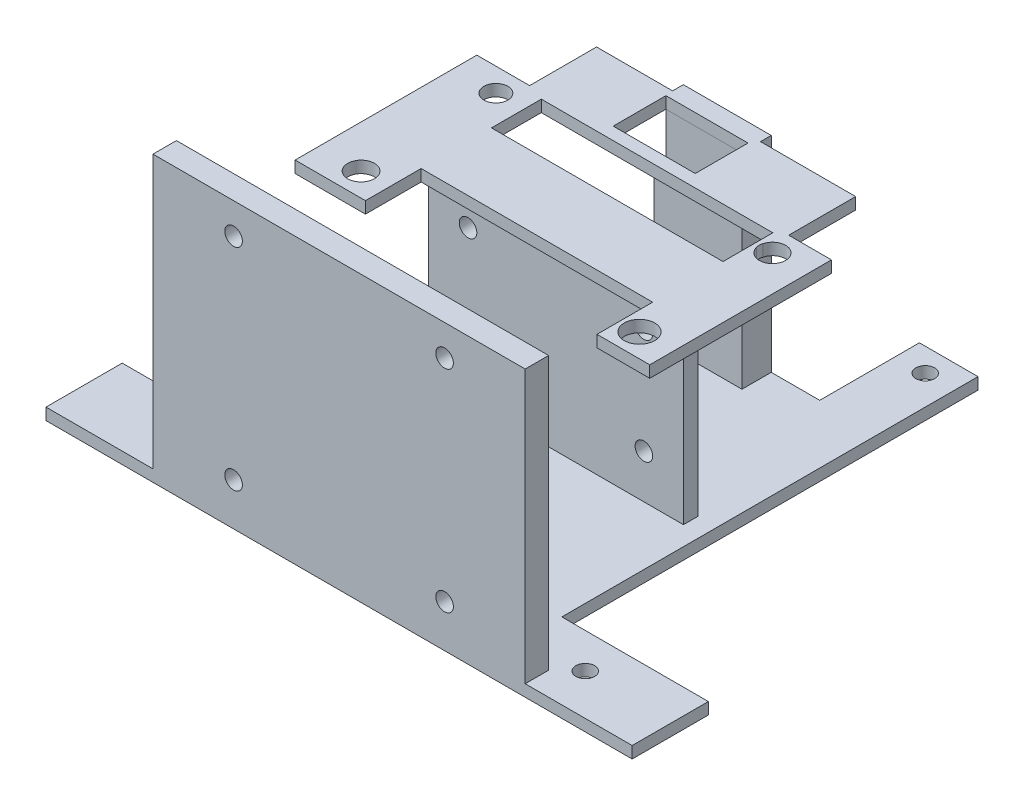
SolidWorks part; units mm, degrees
ref_plane "Alzado" through (0, 0, 0) normal (0, 0, 1) x (1, 0, 0)
ref_plane "Planta" through (0, 0, 0) normal (0, 1, 0) x (1, 0, 0)
ref_plane "Vista lateral" through (0, 0, 0) normal (1, 0, 0) x (0, 0, -1)
sketch "Croquis1" plane through (0, 0, 0) normal (0, 1, 0) x (1, 0, 0)
  line L0 (0, 42) -> (0, -42) construction
  line L1 (-25, 42) -> (25, 42)
  line L2 (-25, 42) -> (-25, -42)
  line L3 (-25, -42) -> (25, -42)
  line L4 (25, 42) -> (25, -42)
  line L5 (-25, -29) -> (-50, -29)
  line L7 (-25, -42) -> (-50, -42)
  line L8 (-50, -29) -> (-50, -42)
  line L13 (-25, 0) -> (25, 0) construction
  line L14 (25, -42) -> (50, -42)
  line L15 (25, -29) -> (50, -29)
  line L16 (50, -29) -> (50, -42)
  dimension "D1" = 84
  dimension "D2" = 50
  dimension "D3" = 13
  dimension "D4" = 25
extrude "Saliente-Extruir1" add sketch "Croquis1" along normal blind 2
sketch "Croquis2" plane through (0, 0, 0) normal (0, 1, 0) x (1, 0, 0)
  line L0 (-25, 42) -> (25, 42) construction
  line L1 (-15, 42) -> (15, 42)
  line L2 (-15, 42) -> (-15, 25)
  line L3 (-15, 25) -> (15, 25)
  line L4 (15, 42) -> (15, 25)
  line L5 (0, 61.3886) -> (0, -18.3687) construction
  dimension "D1" = 30
  dimension "D2" = 17
extrude "Cortar-Extruir1" cut sketch "Croquis2" along normal blind 8
sketch "Croquis4" plane through (0, 0, 0) normal (0, 1, 0) x (1, 0, 0)
  line L1 (-31.75, -42) -> (31.75, -42)
  line L2 (-31.75, -42) -> (-31.75, -38)
  line L3 (-31.75, -38) -> (31.75, -38)
  line L4 (31.75, -42) -> (31.75, -38)
  line L6 (50, -42) -> (-50, -42) construction
  line L7 (0, 53.9436) -> (0, -48.7529) construction
  line L8 (0, 61.3886) -> (0, -18.3687) construction
  dimension "D1" = 63.5
  dimension "D2" = 4
extrude "Saliente-Extruir2" add sketch "Croquis4" along normal blind 48.5
sketch "Croquis5" plane through (0, 0, 0) normal (0, 1, 0) x (1, 0, 0)
  line L1 (-21.75, -2.5) -> (21.75, -2.5)
  line L2 (-21.75, -2.5) -> (-21.75, -5)
  line L3 (-21.75, -5) -> (21.75, -5)
  line L4 (21.75, -2.5) -> (21.75, -5)
  line L5 (-31.75, -38) -> (31.75, -38) construction
  line L7 (0, 6.4821) -> (0, -20.0235) construction
  point P4 (-21.75, -3.75)
  dimension "D1" = 43.5
  dimension "D3" = 2.5
  dimension "D4" = 33
extrude "Saliente-Extruir3" add sketch "Croquis5" along normal blind 35
sketch "Croquis7" plane through (0, 0, 38) normal (0, 0, -1) x (-1, 0, 0)
  line L0 (0, 48.5) -> (0, 2) construction
  line L1 (-31.75, 48.5) -> (31.75, 48.5) construction
  line L2 (-15, 2) -> (15, 2) construction
  line L4 (-18, 7.25) -> (0, 7.25) construction
  line L5 (-31.75, 48.5) -> (-31.75, 2) construction
  line L6 (31.75, 25.25) -> (-31.75, 25.25) construction
  line L7 (31.75, 48.5) -> (31.75, 2) construction
  line L8 (-31.75, 48.5) -> (-31.75, 2) construction
  circle A0 centre (-18, 43.25) radius 1.5
  circle A1 centre (18, 43.25) radius 1.5
  circle A2 centre (18, 7.25) radius 1.5
  circle A3 centre (-18, 7.25) radius 1.5
  dimension "D1" = 3
  dimension "D2" = 18
  dimension "D3" = 36
  dimension "D7" = 13.75
extrude "Cortar-Extruir2" cut sketch "Croquis7" along normal mid plane 18
sketch "Croquis8" plane through (0, 0, 2.5) normal (0, 0, -1) x (-1, 0, 0)
  line L0 (0, 35) -> (0, 2) construction
  line L1 (-21.75, 35) -> (21.75, 35) construction
  line L2 (21.75, 35) -> (21.75, 2) construction
  line L3 (21.75, 2) -> (-21.75, 2) construction
  line L4 (-21.75, 35) -> (-21.75, 2) construction
  line L5 (-21.75, 18.5) -> (21.75, 18.5) construction
  line L6 (15, 27.5) -> (-15, 27.5) construction
  line L7 (-15, 9.5) -> (-15, 27.5) construction
  circle A0 centre (-15, 27.5) radius 1.5
  circle A1 centre (15, 9.5) radius 1.5
  circle A2 centre (15, 27.5) radius 1.5
  circle A3 centre (-15, 9.5) radius 1.5
  dimension "D1" = 9
  dimension "D7" = 3
  dimension "D8" = 30
extrude "Cortar-Extruir3" cut sketch "Croquis8" against normal blind 23
sketch "Croquis12" plane through (0, 35, -35) normal (0, -1, 0) x (1, 0, 0)
  line L0 (0, -26.3886) -> (0, 53.3687) construction
  line L1 (21.25, 44.75) -> (-21.25, 44.75)
  line L3 (21.25, 32.75) -> (-21.25, 32.75)
  line L5 (0, 44.75) -> (0, -0.1804) construction
  line L10 (21.25, 54.25) -> (30.25, 54.25)
  line L11 (21.25, 54.25) -> (21.25, 44.75)
  line L12 (21.25, 23.25) -> (30.25, 23.25)
  line L13 (30.25, 54.25) -> (30.25, 23.25)
  line L24 (-30.25, 54.25) -> (-30.25, 23.25)
  line L25 (-21.25, 23.25) -> (-30.25, 23.25)
  line L26 (-21.25, 54.25) -> (-21.25, 44.75)
  line L27 (-21.25, 54.25) -> (-30.25, 54.25)
  line L28 (21.25, 32.75) -> (21.25, 23.25)
  line L29 (-69.0057, 38.75) -> (69.0057, 38.75) construction
  line L30 (0, -10.5143) -> (0, -10.8047) construction
  line L32 (21.75, 38.75) -> (-21.75, 38.75) construction
  line L33 (21.75, 37.5) -> (21.75, 40) construction
  line L34 (-21.75, 40) -> (-21.75, 37.5) construction
  line L35 (-21.25, 32.75) -> (-21.25, 23.25)
  point P4 (0, 38.75)
  dimension "D1" = 12
  dimension "D2" = 42.5
  dimension "D5" = 31
  dimension "D6" = 9
extrude "Saliente-Extruir4" add sketch "Croquis12" against normal blind 2 separate body
sketch "Croquis13" plane through (0, 37, 0) normal (0, 1, 0) x (1, 0, 0)
  line L1 (30.25, -3.75) -> (-30.25, -3.75) construction
  line L2 (30.25, -19.25) -> (30.25, 11.75) construction
  line L3 (-30.25, -19.25) -> (-30.25, 11.75) construction
  line L4 (0, -9.75) -> (0, 2.25) construction
  line L5 (21.25, -9.75) -> (-21.25, -9.75) construction
  line L6 (21.25, 2.25) -> (-21.25, 2.25) construction
  circle A0 centre (23, -15.25) radius 1.5
  circle A1 centre (23, 7.75) radius 1.5
  circle A2 centre (-23, 7.75) radius 1.5
  circle A3 centre (-23, -15.25) radius 1.5
  dimension "D1" = 3
  dimension "D2" = 11.5
  dimension "D3" = 23
extrude "Cortar-Extruir4" cut sketch "Croquis13" against normal blind 2
sketch "Croquis16" plane through (0, 37, 0) normal (0, 1, 0) x (1, 0, 0)
  line L1 (-21.25, -19.25) -> (-18.25, -19.25)
  line L2 (-21.25, -19.25) -> (-21.25, 11.75)
  line L3 (-21.25, 11.75) -> (-18.25, 11.75)
  line L4 (-18.25, -19.25) -> (-18.25, 11.75)
  dimension "D1" = 3
  dimension "D2" = 31
extrude "Saliente-Extruir7" add sketch "Croquis16" against normal blind 2
sketch "Croquis17" plane through (0, 2, 0) normal (0, 1, 0) x (1, 0, 0)
  line L0 (-15, 25) -> (15, 25) construction
  line L1 (-8.2699, 25) -> (6.7301, 25)
  line L2 (-8.2699, 25) -> (-8.2699, 22)
  line L3 (-8.2699, 22) -> (6.7301, 22)
  line L4 (6.7301, 25) -> (6.7301, 22)
  dimension "D1" = 15
  dimension "D2" = 3
extrude "Saliente-Extruir8" add sketch "Croquis17" along normal blind 25
sketch "Croquis21" plane through (0, 27, 0) normal (0, 1, 0) x (1, 0, 0)
  line L1 (6.7301, 22) -> (-8.2699, 22)
  line L2 (6.7301, 22) -> (6.7301, 25)
  line L3 (6.7301, 25) -> (-8.2699, 25)
  line L4 (-8.2699, 22) -> (-8.2699, 25)
  dimension "D1" = 3
extrude "Saliente-Extruir9" add sketch "Croquis21" along normal blind 2
sketch "Croquis25" plane through (0, 0, -25) normal (0, 0, -1) x (-1, 0, 0)
  circle A0 centre (1.0657, 20.3603) radius 3.8261
extrude "Cortar-Extruir6" cut sketch "Croquis25" against normal blind 2
sketch "Croquis28" plane through (0, 37, 0) normal (0, 1, 0) x (1, 0, 0)
  line L0 (-18.25, 11.75) -> (-30.25, 11.75) construction
  line L1 (-21.2451, 11.75) -> (22.9562, 11.75)
  line L2 (-21.2451, 11.75) -> (-21.2451, 23.1686)
  line L3 (-21.2451, 23.1686) -> (22.9562, 23.1686)
  line L4 (22.9562, 11.75) -> (22.9562, 23.1686)
extrude "Saliente-Extruir10" add sketch "Croquis28" against normal blind 2
sketch "Croquis30" plane through (0, 37, 0) normal (0, 1, 0) x (1, 0, 0)
  line L0 (-15, 25) -> (15, 25) construction
  line L1 (-8.2699, 22) -> (6.7301, 22)
  line L2 (-8.2699, 22) -> (-8.2699, 25)
  line L3 (-8.2699, 25) -> (6.7301, 25)
  line L4 (6.7301, 22) -> (6.7301, 25)
  line L5 (6.7301, 22) -> (6.7301, 25) construction
extrude "Saliente-Extruir11" add sketch "Croquis30" against normal blind 8
sketch "Croquis31" plane through (0, 37, 0) normal (0, 1, 0) x (1, 0, 0)
  line L1 (-8.1292, 21.8914) -> (5.8708, 21.8914)
  line L2 (-8.1292, 21.8914) -> (-8.1292, 12.8914)
  line L3 (-8.1292, 12.8914) -> (5.8708, 12.8914)
  line L4 (5.8708, 21.8914) -> (5.8708, 12.8914)
  dimension "D1" = 9
  dimension "D2" = 14
extrude "Cortar-Extruir7" cut sketch "Croquis31" against normal blind 2
sketch "Croquis33" plane through (0, 37, 0) normal (0, 1, 0) x (1, 0, 0)
  line L0 (-18.25, 2.25) -> (-18.25, 11.75) construction
  line L1 (21.25, 11.75) -> (-18.25, 11.75)
  line L2 (21.25, 11.75) -> (21.25, 10.75)
  line L3 (21.25, 10.75) -> (-18.25, 10.75)
  line L4 (-18.25, 11.75) -> (-18.25, 10.75)
  dimension "D1" = 1
extrude "Saliente-Extruir13" add sketch "Croquis33" against normal blind 2
sketch "Croquis36" plane through (0, 37, 0) normal (0, 1, 0) x (1, 0, 0)
  line L0 (21.25, 2.25) -> (21.25, 10.75) construction
  line L1 (21.25, 9.9483) -> (26.1949, 9.9483)
  line L2 (21.25, 9.9483) -> (21.25, 4.9739)
  line L3 (21.25, 4.9739) -> (26.1949, 4.9739)
  line L4 (26.1949, 9.9483) -> (26.1949, 4.9739)
  circle A0 centre (23.4774, 7.75) radius 1.5667
extrude "Saliente-Extruir14" add sketch "Croquis36" against normal blind 2
sketch "Croquis37" plane through (0, 37, 0) normal (0, 1, 0) x (1, 0, 0)
  circle A0 centre (24.1863, 7.75) radius 2.2423
extrude "Cortar-Extruir8" cut sketch "Croquis37" against normal blind 2
sketch "Croquis38" plane through (0, 37, 0) normal (0, 1, 0) x (1, 0, 0)
  line L0 (21.25, -19.25) -> (21.25, -9.75) construction
  line L1 (21.25, -12.6026) -> (23.1896, -12.6026)
  line L2 (21.25, -12.6026) -> (21.25, -19.25)
  line L3 (21.25, -19.25) -> (23.1896, -19.25)
  line L4 (23.1896, -12.6026) -> (23.1896, -19.25)
  line L5 (21.25, -19.25) -> (30.25, -19.25) construction
extrude "Saliente-Extruir18" add sketch "Croquis38" against normal blind 2
sketch "Croquis39" plane through (0, 37, 0) normal (0, 1, 0) x (1, 0, 0)
  circle A0 centre (24.5, -15.25) radius 2.6084
  arc A1 (23.1896, -16.738) -> (23.1896, -13.762) centre (23, -15.25) ccw construction
extrude "Cortar-Extruir9" cut sketch "Croquis39" against normal blind 2
sketch "Croquis40" plane through (0, 37, 0) normal (0, 1, 0) x (1, 0, 0)
  circle A0 centre (-23, 7.75) radius 2.0455
extrude "Cortar-Extruir10" cut sketch "Croquis40" against normal blind 2
sketch "Croquis41" plane through (0, 37, 0) normal (0, 1, 0) x (1, 0, 0)
  circle A0 centre (-23, -15.25) radius 2.2805
extrude "Cortar-Extruir11" cut sketch "Croquis41" against normal blind 2
sketch "Croquis42" plane through (0, 0, -25) normal (0, 0, -1) x (-1, 0, 0)
  line L1 (-6.7301, 27) -> (8.2699, 27)
  line L2 (-6.7301, 27) -> (-6.7301, 2)
  line L3 (-6.7301, 2) -> (8.2699, 2)
  line L4 (8.2699, 27) -> (8.2699, 2)
extrude "Saliente-Extruir19" add sketch "Croquis42" against normal blind 5
sketch "Croquis43" plane through (0, 2, 0) normal (0, 1, 0) x (1, 0, 0)
  line L0 (-20, 38) -> (20, 38) construction
  line L1 (-35, -35) -> (35, -35) construction
  line L2 (0, 0) -> (0, 70.3147) construction
  line L3 (0, 70.3147) -> (0, -70.7821) construction
  line L4 (-31.75, -42) -> (-50, -42) construction
  circle A0 centre (-20, 38) radius 1.6
  circle A1 centre (20, 38) radius 1.6
  circle A2 centre (-35, -35) radius 1.6
  circle A3 centre (35, -35) radius 1.6
  point P10 (0, 38)
  point P13 (0, -35)
  dimension "D1" = 3.2
  dimension "D6" = 7
  dimension "D2" = 35
  dimension "D3" = 35
  dimension "D4" = 38
  dimension "D5" = 20
extrude "Cortar-Extruir12" cut sketch "Croquis43" against normal blind 10
